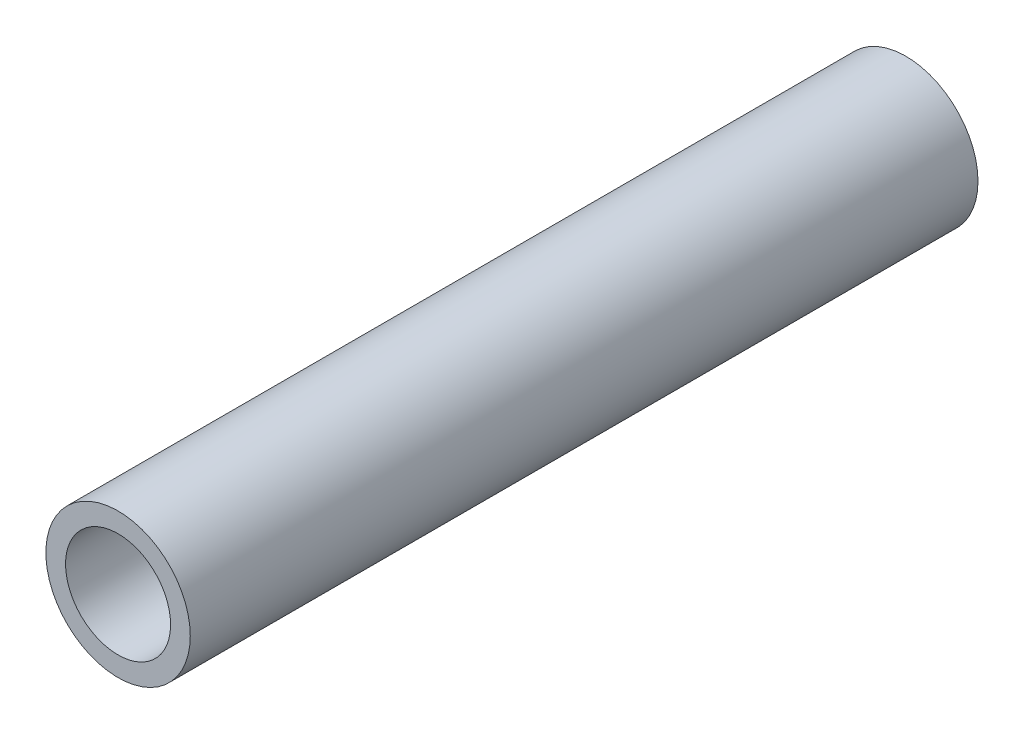
SolidWorks part; units mm, degrees
ref_plane "Front Plane" through (0, 0, 0) normal (0, 0, 1) x (1, 0, 0)
ref_plane "Top Plane" through (0, 0, 0) normal (0, 1, 0) x (1, 0, 0)
ref_plane "Right Plane" through (0, 0, 0) normal (1, 0, 0) x (0, 0, -1)
sketch "Sketch1" plane through (0, 0, 0) normal (0, 0, 1) x (1, 0, 0)
  circle A0 centre (0, 0) radius 8
  circle A1 centre (0, 0) radius 11
  dimension "D1" = 16
  dimension "D2" = 22
extrude "Boss-Extrude1" add sketch "Sketch1" along normal mid plane 120
